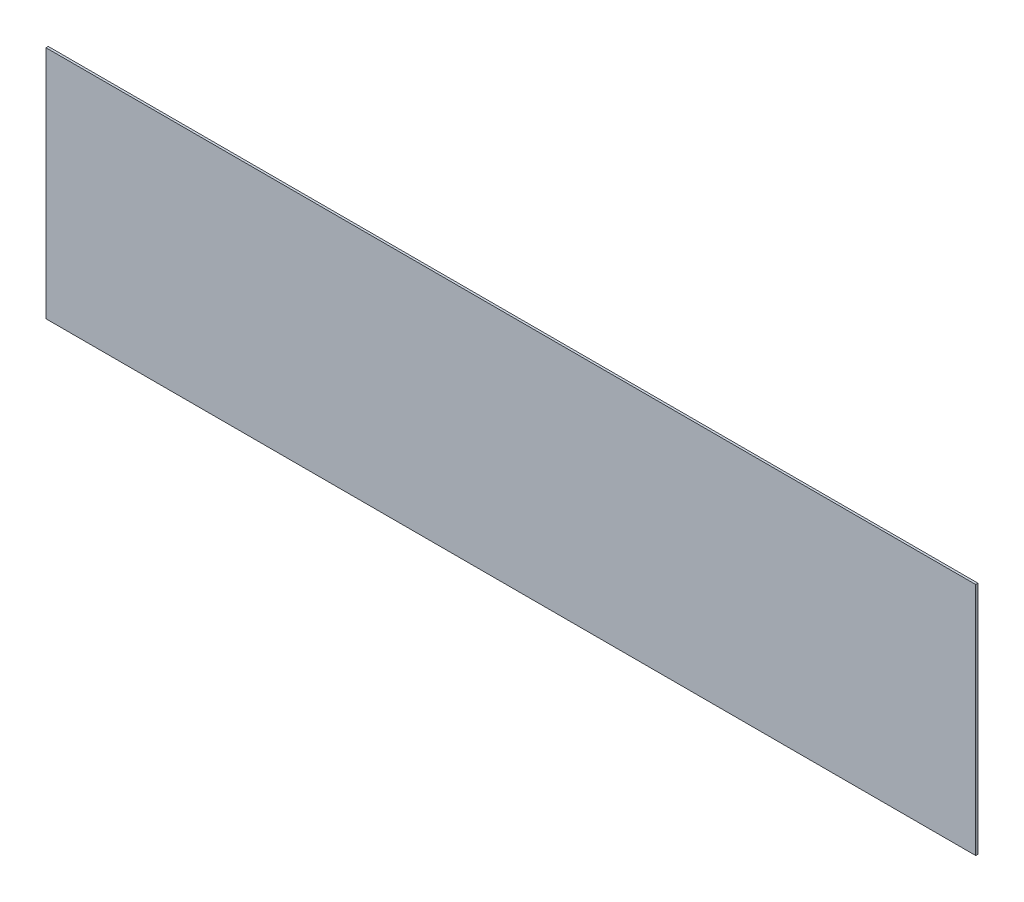
SolidWorks part; units mm, degrees
ref_plane "Front Plane" through (0, 0, 0) normal (0, 0, 1) x (1, 0, 0)
ref_plane "Top Plane" through (0, 0, 0) normal (0, 1, 0) x (1, 0, 0)
ref_plane "Right Plane" through (0, 0, 0) normal (1, 0, 0) x (0, 0, -1)
sketch "Sketch2" plane through (0, 0, 0) normal (0, 0, 1) x (1, 0, 0)
  line L1 (0, 0) -> (203.2, 0)
  line L2 (0, 0) -> (0, 51.308)
  line L3 (0, 51.308) -> (203.2, 51.308)
  line L4 (203.2, 0) -> (203.2, 51.308)
  dimension "D1" = 51.308
  dimension "D2" = 203.2
extrude "Boss-Extrude1" add sketch "Sketch2" along normal blind 0.5
